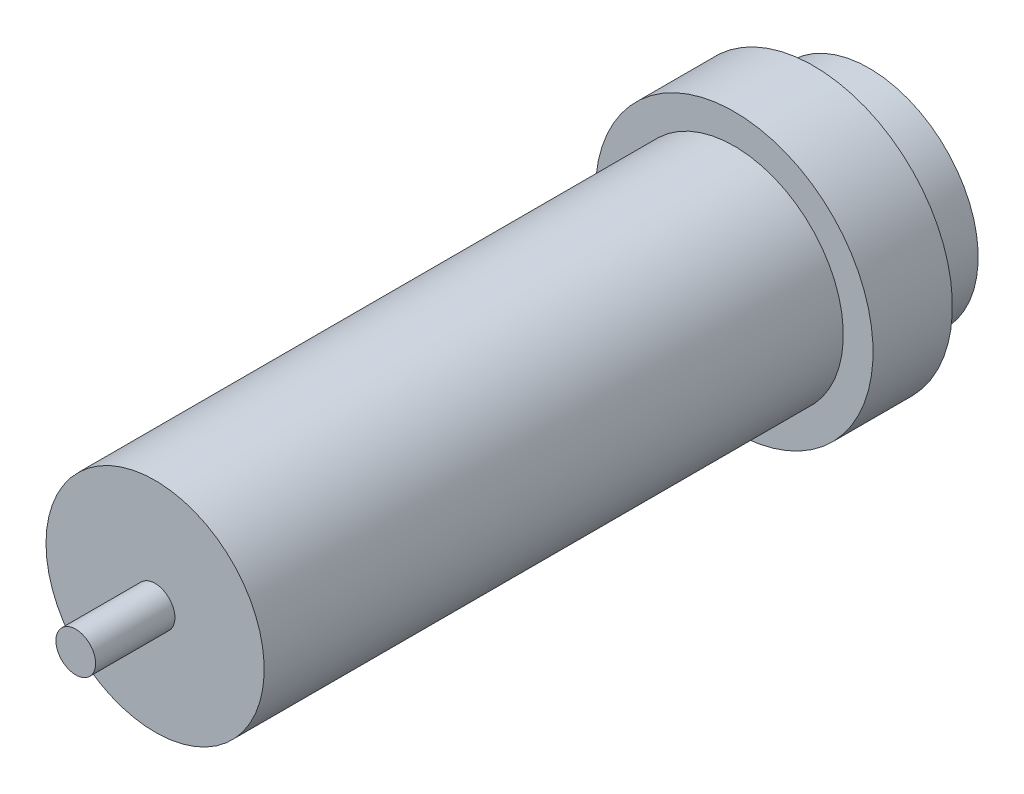
SolidWorks part; units mm, degrees
ref_plane "Front Plane" through (0, 0, 0) normal (0, 0, 1) x (1, 0, 0)
ref_plane "Top Plane" through (0, 0, 0) normal (0, 1, 0) x (1, 0, 0)
ref_plane "Right Plane" through (0, 0, 0) normal (1, 0, 0) x (0, 0, -1)
sketch "Sketch1" plane through (0, 0, 0) normal (0, 0, 1) x (1, 0, 0)
  circle A0 centre (0, 0) radius 5
  dimension "D1" = 10
extrude "Boss-Extrude1" add sketch "Sketch1" along normal blind 10 contours A0
sketch "Sketch2" plane through (0, 0, 10) normal (0, 0, 1) x (1, 0, 0)
  circle A0 centre (0, 0) radius 27.5
  dimension "D1" = 55
extrude "Boss-Extrude2" add sketch "Sketch2" along normal blind 180
ref_plane "Plane1" through (0, 0, 34) normal (0, 0, -1) x (-1, 0, 0)
sketch "Sketch3" plane through (0, 0, 34) normal (0, 0, -1) x (-1, 0, 0)
  circle A0 centre (0, 0) radius 35
  dimension "D1" = 70
extrude "Boss-Extrude3" add sketch "Sketch3" along normal blind 10 and the other way blind 10
sketch "Sketch5" plane through (0, 0, 190) normal (0, 0, 1) x (1, 0, 0)
  circle A0 centre (0, 0) radius 5
  dimension "D1" = 10
extrude "Boss-Extrude4" add sketch "Sketch5" along normal blind 20
ref_plane "Plane2" through (0, 0, 176) normal (0, 0, 1) x (1, 0, 0)
sketch "Sketch7" plane through (0, 0, 176) normal (0, 0, 1) x (1, 0, 0)
  line L0 (-35, 0) -> (35, 0)
  circle A0 centre (0, 0) radius 35 construction
